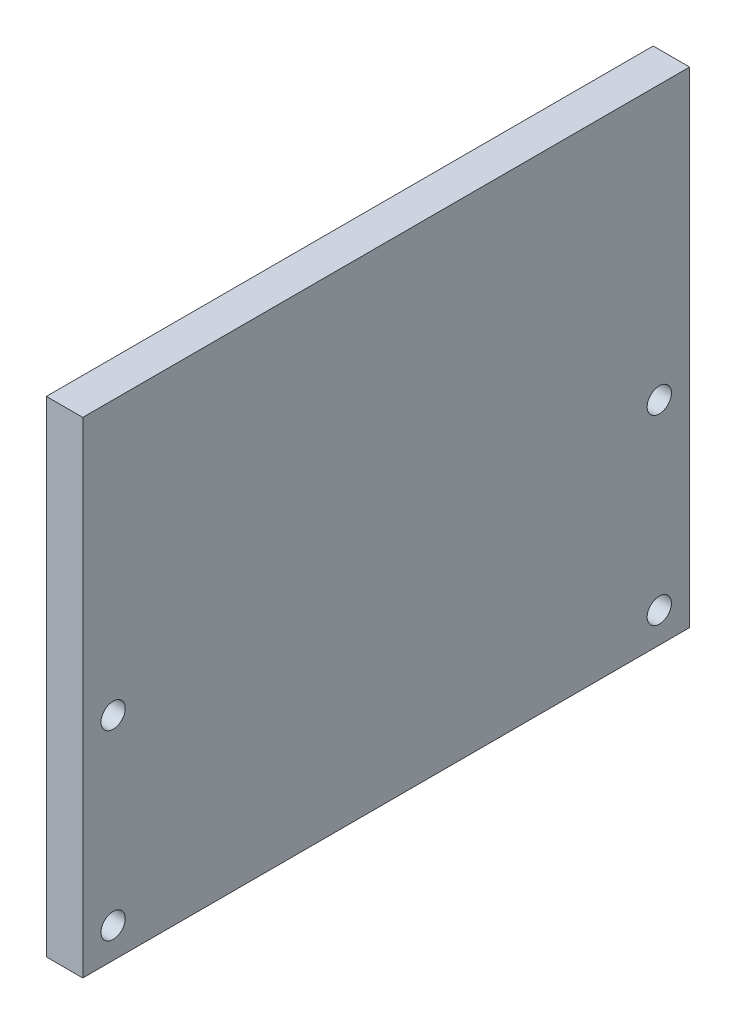
SolidWorks part; units mm, degrees
ref_plane "Alzado" through (0, 0, 0) normal (0, 0, 1) x (1, 0, 0)
ref_plane "Planta" through (0, 0, 0) normal (0, 1, 0) x (1, 0, 0)
ref_plane "Vista lateral" through (0, 0, 0) normal (1, 0, 0) x (0, 0, -1)
sketch "Croquis1" plane through (0, 0, 0) normal (1, 0, 0) x (0, 0, -1)
  line L0 (-3.5256, 0) -> (-62.6603, 0) construction
  line L1 (-0.9615, 0) -> (-0.9615, 42.8686) construction
  line L2 (-25.9615, 0) -> (-25.9615, 20)
  line L3 (-25.9615, 20) -> (-0.9615, 20)
  line L4 (-0.9615, 20) -> (24.0385, 20)
  line L5 (24.0385, 20) -> (24.0385, 0)
  line L6 (-25.9615, 0) -> (-25.9615, -20)
  line L7 (-25.9615, -20) -> (24.0385, -20)
  line L8 (24.0385, -20) -> (24.0385, 0)
  line L9 (-25.9615, -10) -> (24.0385, -10) construction
  circle A0 centre (-23.4615, -17.5) radius 1
  circle A1 centre (21.5385, -17.5) radius 1
  circle A2 centre (21.5385, -2.5) radius 1
  circle A3 centre (-23.4615, -2.5) radius 1
  dimension "D1" = 25
  dimension "D3" = 2.5
  dimension "D8" = 2
  dimension "D2" = 25
  dimension "D4" = 2.5
  dimension "D5" = 20
  dimension "D6" = 20
  dimension "D7" = 10
extrude "Saliente-Extruir3" add sketch "Croquis1" along normal blind 3
